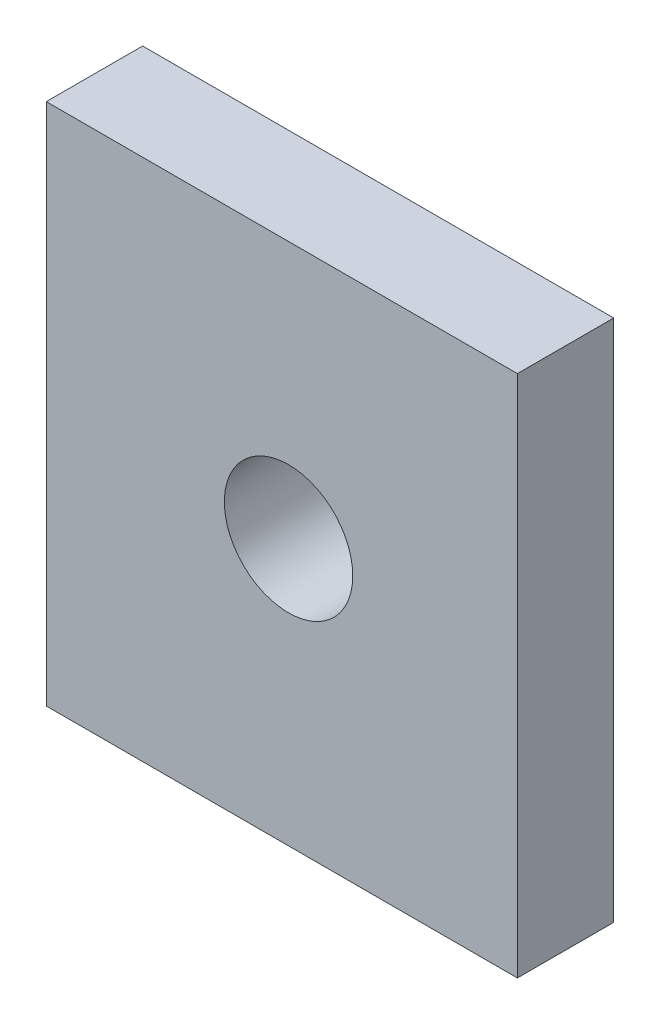
SolidWorks part; units mm, degrees
ref_plane "Front Plane" through (0, 0, 0) normal (0, 0, 1) x (1, 0, 0)
ref_plane "Top Plane" through (0, 0, 0) normal (0, 1, 0) x (1, 0, 0)
ref_plane "Right Plane" through (0, 0, 0) normal (1, 0, 0) x (0, 0, -1)
sketch "Sketch1" plane through (0, 0, 0) normal (0, 0, 1) x (1, 0, 0)
  line L1 (-37.727, 40.0968) -> (35.6416, 40.0968)
  line L2 (-37.727, 40.0968) -> (-37.727, -41.4238)
  line L3 (-37.727, -41.4238) -> (35.6416, -41.4238)
  line L4 (35.6416, 40.0968) -> (35.6416, -41.4238)
  circle A0 centre (0, 0) radius 10
extrude "Boss-Extrude1" add sketch "Sketch1" along normal blind 15
